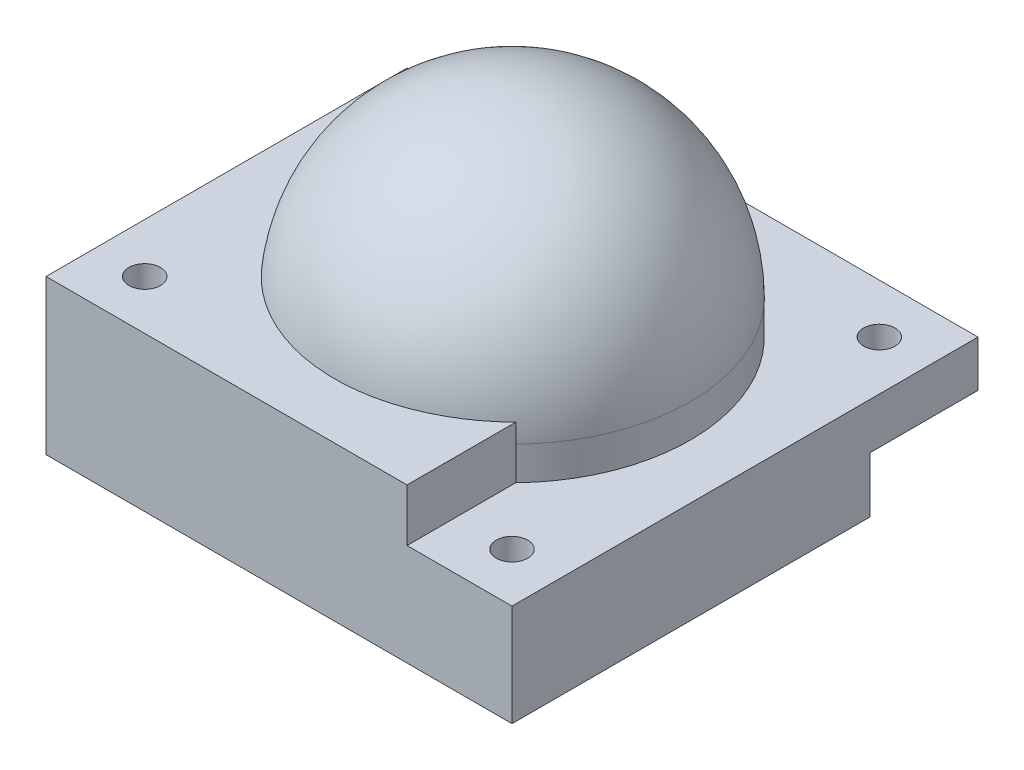
SolidWorks part; units mm, degrees
ref_plane "Front Plane" through (0, 0, 0) normal (0, 0, 1) x (1, 0, 0)
ref_plane "Top Plane" through (0, 0, 0) normal (0, 1, 0) x (1, 0, 0)
ref_plane "Right Plane" through (0, 0, 0) normal (1, 0, 0) x (0, 0, -1)
sketch "Sketch2" plane through (0, 0, 0) normal (0, 0, 1) x (1, 0, 0)
  line L0 (-10, 0) -> (-12, 0)
  line L1 (-17, 0) -> (-17, -3.175)
  line L2 (-17, -3.175) -> (-10, -3.175)
  line L3 (-10, -3.175) -> (-10, 0)
  line L4 (0, 12) -> (0, 17)
  arc A0 (0, 12) -> (-12, 0) centre (0, 0) ccw
  arc A1 (0, 17) -> (-17, 0) centre (0, 0) ccw
  dimension "D1" = 24
  dimension "D2" = 34
  dimension "D3" = 3.175
  dimension "D4" = 7
revolve "Revolve1" add sketch "Sketch2" angle 360 about L4
sketch "Sketch3" plane through (0, -3.175, 0) normal (0, -1, 0) x (1, 0, 0)
  line L1 (-22.2, 22.2) -> (22.2, 22.2)
  line L2 (-22.2, 22.2) -> (-22.2, -22.2)
  line L3 (-22.2, -22.2) -> (22.2, -22.2)
  line L4 (22.2, 22.2) -> (22.2, -22.2)
  circle A0 centre (0, 0) radius 10 construction
  dimension "D1" = 44.4
  dimension "D2" = 44.4
  dimension "D3" = 22.2
  dimension "D4" = 22.2
extrude "Boss-Extrude1" add sketch "Sketch3" along normal blind 9.7
sketch "Sketch4" plane through (0, -12.875, 0) normal (0, -1, 0) x (1, 0, 0)
  line L1 (22.2, -22.2) -> (11.9, -22.2)
  line L2 (22.2, -22.2) -> (22.2, -11.9)
  line L3 (22.2, -11.9) -> (11.9, -11.9)
  line L4 (11.9, -22.2) -> (11.9, -11.9)
  dimension "D1" = 10.3
  dimension "D2" = 10.3
extrude "Cut-Extrude1" cut sketch "Sketch4" against normal blind 5.3
sketch "Sketch5" plane through (0, -12.875, 0) normal (0, -1, 0) x (1, 0, 0)
  line L0 (-22.2, -22.2) -> (11.9, -22.2) construction
  line L1 (22.2, -11.9) -> (22.2, 22.2) construction
  circle A0 centre (0, 0) radius 6
  dimension "D1" = 22.2
  dimension "D2" = 22.2
  dimension "D3" = 12
extrude "Cut-Extrude2" cut sketch "Sketch5" against normal blind 14.3
sketch "Sketch6" plane through (0, -3.175, 0) normal (0, 1, 0) x (1, 0, 0)
  line L0 (-22.2, -22.2) -> (-22.2, 12.2)
  line L1 (-22.2, -22.2) -> (-22.2, 22.2) construction
  line L2 (-22.2, -22.2) -> (12.2, -22.2)
  line L3 (22.2, -22.2) -> (-22.2, -22.2) construction
  line L6 (12.2, -22.2) -> (12.2, -11.83)
  line L7 (-22.2, 12.2) -> (-11.83, 12.2)
  arc A2 (12.2, -11.83) -> (-11.83, 12.2) centre (0.185, 0.185) cw
  dimension "D1" = 34.4
  dimension "D2" = 34.4
  dimension "D3" = 10.37
  dimension "D4" = 10.37
extrude "Boss-Extrude2" add sketch "Sketch6" along normal blind 5
sketch "Sketch7" plane through (0, 1.825, 0) normal (0, 1, 0) x (1, 0, 0)
  line L0 (22.2, 22.2) -> (22.2, -22.2) construction
  line L1 (-22.2, 22.2) -> (22.2, 22.2) construction
  line L2 (-22.2, 12.2) -> (-22.2, 22.2) construction
  line L3 (-22.2, 12.2) -> (-22.2, -22.2) construction
  line L4 (-22.2, -22.2) -> (12.2, -22.2) construction
  line L5 (22.2, -22.2) -> (12.2, -22.2) construction
  circle A0 centre (-17.5, -17.5) radius 1.5
  circle A1 centre (17.5, -17.5) radius 1.5
  circle A2 centre (17.5, 17.5) radius 1.5
  circle A3 centre (-17.5, 17.5) radius 1.5
  dimension "D1" = 3
  dimension "D2" = 3
  dimension "D3" = 3
  dimension "D4" = 3
  dimension "D5" = 4.7
  dimension "D6" = 4.7
  dimension "D7" = 4.7
  dimension "D8" = 4.7
  dimension "D9" = 4.7
  dimension "D10" = 4.7
  dimension "D11" = 4.7
  dimension "D12" = 4.7
extrude "Cut-Extrude3" cut sketch "Sketch7" against normal through all both and the other way through all
